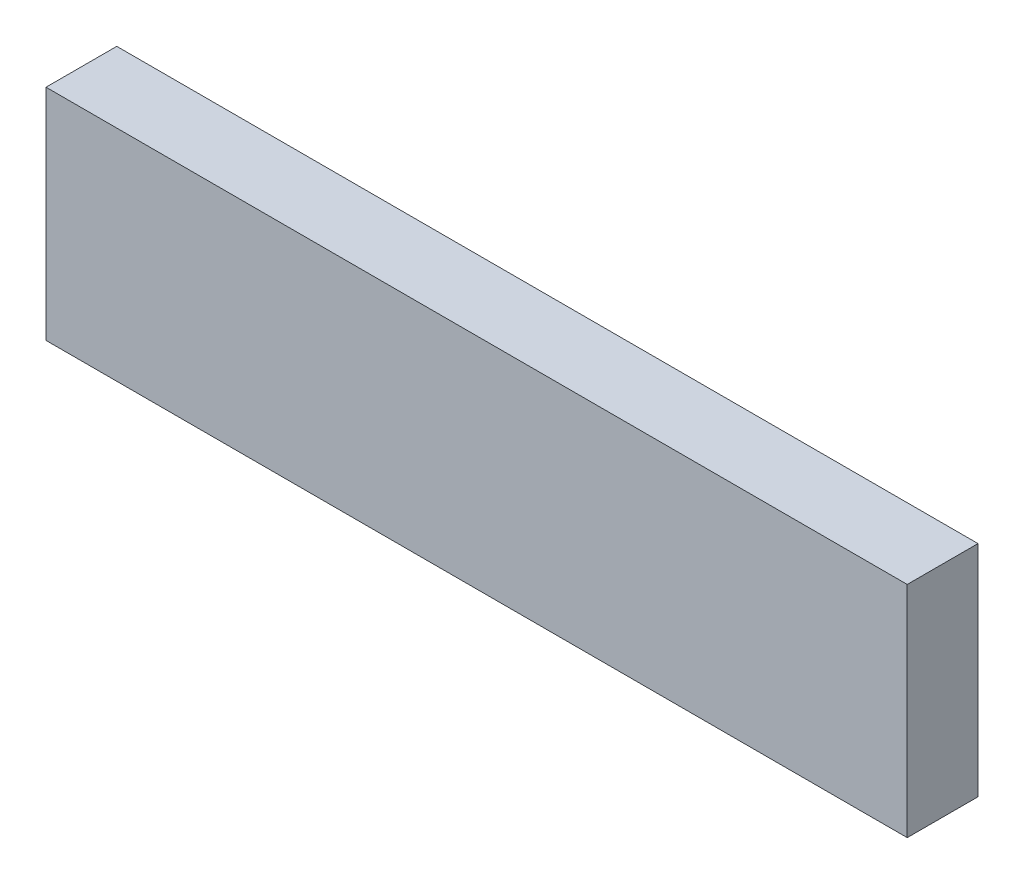
SolidWorks part; units mm, degrees
ref_plane "Front Plane" through (0, 0, 0) normal (0, 0, 1) x (1, 0, 0)
ref_plane "Top Plane" through (0, 0, 0) normal (0, 1, 0) x (1, 0, 0)
ref_plane "Right Plane" through (0, 0, 0) normal (1, 0, 0) x (0, 0, -1)
sketch "Sketch1" plane through (0, 0, 0) normal (0, 0, 1) x (1, 0, 0)
  line L0 (0.0127, 3.1166) -> (12.1818, 3.1166)
  line L1 (12.1818, 3.1166) -> (12.1818, 0.0178)
  line L2 (12.1818, 0.0178) -> (0.0127, 0.0178)
  line L3 (0.0127, 0.0178) -> (0.0127, 3.1166)
extrude "Component_Outline" add sketch "Sketch1" along normal blind 1 separate body
sketch3d "3DSketch1"
  line L0 (0, 0, 0) -> (1, 0, 0)
  line L1 (0, 0, 0) -> (0, 1, 0)
  line L2 (0, 0, 0) -> (0, 0, 1)
  point P0 (0, 0, 0)
